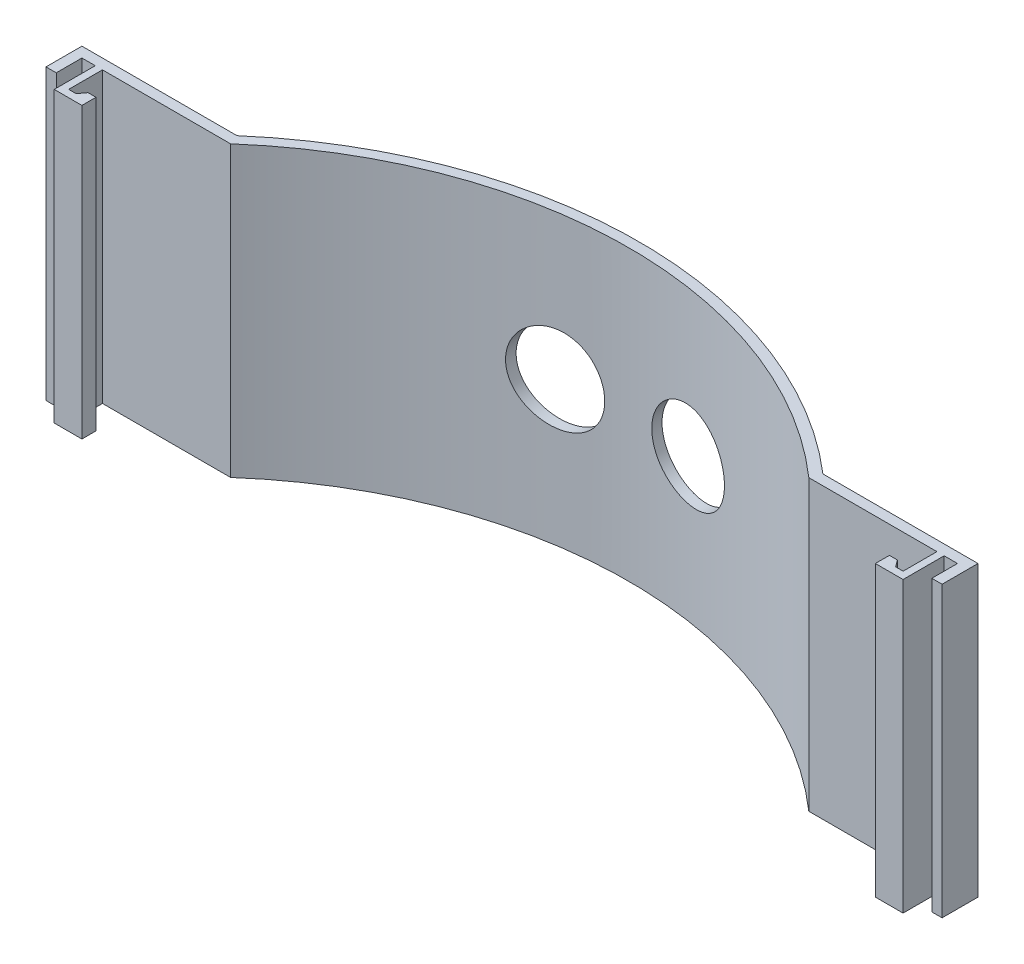
SolidWorks part; units mm, degrees
ref_plane "Front Plane" through (0, 0, 0) normal (0, 0, 1) x (1, 0, 0)
ref_plane "Top Plane" through (0, 0, 0) normal (0, 1, 0) x (1, 0, 0)
ref_plane "Right Plane" through (0, 0, 0) normal (1, 0, 0) x (0, 0, -1)
sketch "Sketch1" plane through (0, 0, 0) normal (0, 1, 0) x (1, 0, 0)
  line L0 (0, 85.2249) -> (0, 0) construction
  line L1 (-85.3, 58.95) -> (-87.3, 58.95)
  line L2 (-87.3, 58.95) -> (-87.3, 65.95)
  line L5 (-83, 63.65) -> (-83, 55.65) construction
  line L6 (-83, 55.65) -> (-77, 55.65) construction
  line L7 (-77, 55.65) -> (-77, 58.9927) construction
  line L8 (-77, 58.9927) -> (-79, 58.9927) construction
  line L9 (-79, 58.9927) -> (-80, 57.6594) construction
  line L10 (-80, 57.6594) -> (-81, 57.6594) construction
  line L11 (-81, 57.6594) -> (-81, 63.65) construction
  line L12 (-81, 63.65) -> (-56.3354, 63.65) construction
  line L13 (-83, 63.65) -> (-85, 63.65) construction
  line L14 (-85, 63.65) -> (-85, 58.95) construction
  line L15 (-85, 63.65) -> (-85, -63.65) construction
  line L16 (-85.3, 63.95) -> (-85.3, 58.95)
  line L17 (-82.7, 63.95) -> (-85.3, 63.95)
  line L18 (-82.7, 63.95) -> (-82.7, 55.95)
  line L19 (-82.7, 55.95) -> (-77.3, 55.95)
  line L20 (-77.3, 55.95) -> (-77.3, 58.6927)
  line L21 (-77.3, 58.6927) -> (-78.85, 58.6927)
  line L22 (-78.85, 58.6927) -> (-79.85, 57.3594)
  line L23 (-79.85, 57.3594) -> (-81.3, 57.3594)
  line L24 (-81.3, 57.3594) -> (-81.3, 63.95)
  line L25 (-81.3, 63.95) -> (-56.3354, 63.95)
  line L26 (85, 63.65) -> (85, 58.95) construction
  line L27 (-82, 65.95) -> (-87.3, 65.95)
  line L28 (-82, 65.95) -> (-82, 65.95)
  line L29 (-82, 65.95) -> (-82, 65.95)
  line L30 (-82, 65.95) -> (-82, 65.95)
  line L31 (-82, 65.95) -> (-82, 65.95)
  line L32 (-82, 65.95) -> (-82, 65.95)
  line L33 (-82, 65.95) -> (-82, 65.95)
  line L34 (-82, 65.95) -> (-82, 65.95)
  line L35 (-82, 65.95) -> (-57.0857, 65.95)
  line L36 (-87.3, 60.95) -> (-89.1124, 60.95) construction
  line L37 (-85.3, 58.95) -> (-89.1124, 58.95) construction
  line L38 (-87.3, 65.95) -> (-87.3, 60.95) construction
  line L39 (83, 63.65) -> (85, 63.65) construction
  line L40 (81, 63.65) -> (56.3354, 63.65) construction
  line L41 (81, 57.6594) -> (81, 63.65) construction
  line L42 (80, 57.6594) -> (81, 57.6594) construction
  line L43 (79, 58.9927) -> (80, 57.6594) construction
  line L44 (77, 58.9927) -> (79, 58.9927) construction
  line L45 (77, 55.65) -> (77, 58.9927) construction
  line L46 (83, 55.65) -> (77, 55.65) construction
  line L47 (83, 63.65) -> (83, 55.65) construction
  line L48 (82, 65.95) -> (57.0857, 65.95)
  line L49 (82, 65.95) -> (87.3, 65.95)
  line L50 (81.3, 63.95) -> (56.3354, 63.95)
  line L51 (81.3, 57.3594) -> (81.3, 63.95)
  line L52 (79.85, 57.3594) -> (81.3, 57.3594)
  line L53 (78.85, 58.6927) -> (79.85, 57.3594)
  line L54 (77.3, 58.6927) -> (78.85, 58.6927)
  line L55 (77.3, 55.95) -> (77.3, 58.6927)
  line L56 (82.7, 55.95) -> (77.3, 55.95)
  line L57 (82.7, 63.95) -> (82.7, 55.95)
  line L58 (82.7, 63.95) -> (85.3, 63.95)
  line L59 (85.3, 63.95) -> (85.3, 58.95)
  line L60 (87.3, 58.95) -> (87.3, 65.95)
  line L61 (85.3, 58.95) -> (87.3, 58.95)
  arc A0 (-56.3354, 63.95) -> (0, 85.2249) centre (0, 0) cw
  arc A1 (-57.0857, 65.95) -> (0, 87.2249) centre (0, 0) cw
  arc A2 (57.0857, 65.95) -> (0, 87.2249) centre (0, 0) ccw
  arc A3 (56.3354, 63.95) -> (0, 85.2249) centre (0, 0) ccw
  dimension "D1" = 2
  dimension "D5" = 5
  dimension "D4" = 0.3
extrude "Boss-Extrude1" add sketch "Sketch1" along normal blind 56.3
sketch "Sketch2" plane through (0, 0, -55.95) normal (0, 0, 1) x (1, 0, 0)
  line L0 (-87.3, 28.15) -> (87.3, 28.15) construction
  line L1 (-87.3, 56.3) -> (-87.3, 0) construction
  line L2 (87.3, 56.3) -> (87.3, 0) construction
  line L3 (0, 0) -> (0, 28.15) construction
  circle A0 centre (12.955, 28.15) radius 8.37
  circle A1 centre (-12.955, 28.15) radius 8.37
  dimension "D2" = 16.74
  dimension "D1" = 25.91
extrude "Cut-Extrude1" cut sketch "Sketch2" against normal through all
equation "\"D1@Boss-Extrude1\"=45.3+11"
